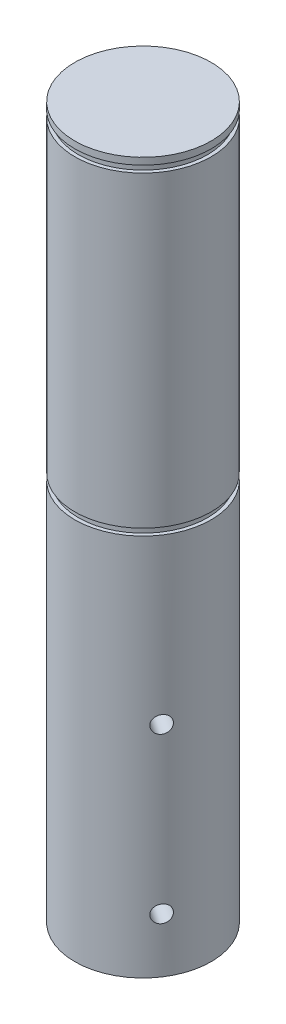
SolidWorks part; units mm, degrees
material "延性铁"
ref_plane "前视基准面" through (0, 0, 0) normal (0, 0, 1) x (1, 0, 0)
ref_plane "上视基准面" through (0, 0, 0) normal (0, 1, 0) x (1, 0, 0)
ref_plane "右视基准面" through (0, 0, 0) normal (1, 0, 0) x (0, 0, -1)
sketch "草图1" plane through (0, 0, 0) normal (0, 1, 0) x (1, 0, 0)
  circle A0 centre (5.9, 0) radius 9.975
  dimension "D1" = 19.95
extrude "凸台-拉伸1" add sketch "草图1" along normal blind 40
ref_plane "基准面1" through (0, 20, 0) normal (0, -1, 0) x (-1, 0, 0)
hole_wizard "M3 螺纹孔2" positions "3D草图2" profile "草图4" tap size "M3" standard "GB"
sketch3d "3D草图2"
  point P0 (14.1913, 8, 5.5457)
  dimension "D1" = 8
sketch "草图4" plane through (14.1913, 8, 5.5457) normal (0, 1, 0) x (0.556, 0, -0.8312)
  line L0 (0, 0) -> (0, 9.2511)
  line L1 (0, 9.2511) -> (1.25, 8.5)
  line L2 (1.25, 8.5) -> (1.25, 0)
  line L5 (1.25, 0) -> (0, 0)
  line L10 (0, 9.2511) -> (-1.25, 8.5) construction
  line L11 (0, -6.35) -> (0, 107.95) construction
  dimension "螺纹孔钻头直径" = 2.5
  dimension "螺纹孔钻头深度" = 8.5
  dimension "导头角度" = 118
cosmetic thread "孔螺蚊线4" parameters "D1"=6, "D2"=3
mirror "螺纹孔镜向" about plane through (0, 20, 0) normal (0, -1, 0) of "M3 螺纹孔2"
sketch "草图5" plane through (0, 40, 0) normal (0, 1, 0) x (1, 0, 0)
  circle A0 centre (5.9, 0) radius 9.975
  dimension "D1" = 19.95
extrude "16mm 铰链间距" add sketch "草图5" along normal blind 16
sketch "草图6" plane through (0, 56, 0) normal (0, 1, 0) x (1, 0, 0)
  circle A0 centre (5.9, 0) radius 9.45
  circle A1 centre (5.9, 0) radius 9.975 construction
  dimension "D1" = 18.9
extrude "卡簧1" add sketch "草图6" along normal blind 1
sketch "草图7" plane through (0, 57, 0) normal (0, 1, 0) x (1, 0, 0)
  circle A0 centre (5.9, 0) radius 9.975
  dimension "D1" = 19.95
extrude "凸台-拉伸4" add sketch "草图7" along normal blind 45
sketch "草图8" plane through (0, 102, 0) normal (0, 1, 0) x (1, 0, 0)
  circle A0 centre (5.9, 0) radius 9.45
  dimension "D1" = 18.9
extrude "卡簧2" add sketch "草图8" along normal blind 1
sketch "草图9" plane through (0, 103, 0) normal (0, 1, 0) x (1, 0, 0)
  circle A0 centre (5.9, 0) radius 9.975
  circle A1 centre (5.9, 0) radius 9.45 construction
  dimension "D1" = 19.95
extrude "凸台-拉伸6" add sketch "草图9" along normal blind 1
